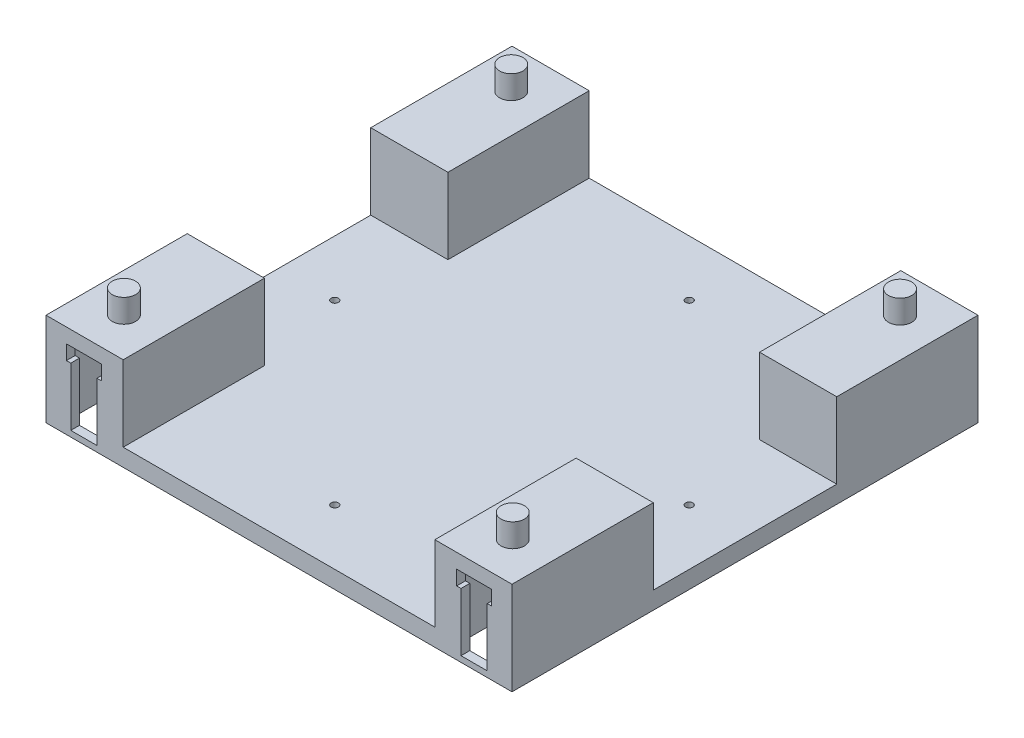
SolidWorks part; units mm, degrees
material "ABS"
ref_plane "Front Plane" through (0, 0, 0) normal (0, 0, 1) x (1, 0, 0)
ref_plane "Top Plane" through (0, 0, 0) normal (0, 1, 0) x (1, 0, 0)
ref_plane "Right Plane" through (0, 0, 0) normal (1, 0, 0) x (0, 0, -1)
sketch "Sketch2" plane through (0, 0, 0) normal (0, 1, 0) x (1, 0, 0)
  line L1 (-80, -80) -> (80, -80)
  line L2 (-80, -80) -> (-80, 80)
  line L3 (-80, 80) -> (80, 80)
  line L4 (80, -80) -> (80, 80)
  line L5 (-80, -80) -> (80, 80) construction
  line L6 (-80, 80) -> (80, -80) construction
  point P0 (0, 0)
  dimension "D1" = 160
  dimension "D2" = 160
extrude "Boss-Extrude2" add sketch "Sketch2" along normal blind 6
sketch "Sketch3" plane through (0, 0, 0) normal (0, 1, 0) x (1, 0, 0)
  line L22 (0, 25.1839) -> (0, 0) construction
  line L23 (-80, 80) -> (-53.5, 80)
  line L24 (-80, 80) -> (-80, 31.5)
  line L25 (-80, 31.5) -> (-53.5, 31.5)
  line L26 (-53.5, 80) -> (-53.5, 31.5)
  line L27 (0, 0) -> (14.719, 0) construction
  line L28 (53.5, 80) -> (53.5, 31.5)
  line L29 (80, 31.5) -> (53.5, 31.5)
  line L30 (80, 80) -> (80, 31.5)
  line L31 (80, 80) -> (53.5, 80)
  line L32 (80, -80) -> (53.5, -80)
  line L33 (80, -80) -> (80, -31.5)
  line L34 (80, -31.5) -> (53.5, -31.5)
  line L35 (53.5, -80) -> (53.5, -31.5)
  line L36 (-53.5, -80) -> (-53.5, -31.5)
  line L37 (-80, -31.5) -> (-53.5, -31.5)
  line L38 (-80, -80) -> (-80, -31.5)
  line L39 (-80, -80) -> (-53.5, -80)
  dimension "D1" = 26.5
  dimension "D2" = 48.5
extrude "Boss-Extrude3" add sketch "Sketch3" along normal blind 32
sketch "Sketch4" plane through (0, 0, 0) normal (0, 1, 0) x (1, 0, 0)
  line L8 (0, 18.9879) -> (0, 0) construction
  line L9 (-77, 77) -> (-56.5, 77)
  line L22 (-77, 77) -> (-77, 34.5)
  line L23 (-77, 34.5) -> (-56.5, 34.5)
  line L24 (-56.5, 77) -> (-56.5, 34.5)
  line L25 (0, 0) -> (16.3713, 0) construction
  line L26 (-80, 80) -> (-80, 31.5) construction
  line L27 (-53.5, 80) -> (-80, 80) construction
  line L29 (-53.5, 80) -> (-80, 31.5) construction
  line L30 (-56.5, 34.5) -> (-77, 77) construction
  line L31 (56.5, 34.5) -> (77, 77) construction
  line L32 (53.5, 80) -> (80, 31.5) construction
  line L33 (56.5, 77) -> (56.5, 34.5)
  line L34 (77, 34.5) -> (56.5, 34.5)
  line L35 (77, 77) -> (77, 34.5)
  line L36 (77, 77) -> (56.5, 77)
  line L37 (53.5, -80) -> (80, -31.5) construction
  line L38 (56.5, -34.5) -> (77, -77) construction
  line L39 (-56.5, -34.5) -> (-77, -77) construction
  line L40 (-53.5, -80) -> (-80, -31.5) construction
  line L41 (77, -77) -> (56.5, -77)
  line L42 (77, -77) -> (77, -34.5)
  line L43 (77, -34.5) -> (56.5, -34.5)
  line L44 (56.5, -77) -> (56.5, -34.5)
  line L45 (-56.5, -77) -> (-56.5, -34.5)
  line L46 (-77, -34.5) -> (-56.5, -34.5)
  line L47 (-77, -77) -> (-77, -34.5)
  line L48 (-77, -77) -> (-56.5, -77)
  point P11 (-66.75, 55.75)
  point P12 (-66.75, 55.75)
  dimension "D1" = 3
  dimension "D2" = 3
extrude "Cut-Extrude2" cut sketch "Sketch4" along normal blind 29
sketch "Sketch5" plane through (0, 32, 0) normal (0, 1, 0) x (1, 0, 0)
  line L0 (-66.75, 80) -> (-66.75, 66.5) construction
  line L1 (-80, 80) -> (-53.5, 80) construction
  line L2 (20.1859, 0) -> (0, 0) construction
  line L3 (0, 0) -> (0, 23.6816) construction
  line L4 (66.75, 80) -> (66.75, 66.5) construction
  line L5 (66.75, -80) -> (66.75, -66.5) construction
  line L6 (-66.75, -80) -> (-66.75, -66.5) construction
  circle A1 centre (-66.75, 66.5) radius 4
  circle A2 centre (66.75, 66.5) radius 4
  circle A3 centre (66.75, -66.5) radius 4
  circle A4 centre (-66.75, -66.5) radius 4
  dimension "D1" = 8
  dimension "D2" = 13.5
extrude "Boss-Extrude4" add sketch "Sketch5" along normal blind 8
sketch "Sketch6" plane through (0, 0, 80) normal (0, 0, 1) x (1, 0, 0)
  line L8 (-53.5, 6) -> (-80, 6) construction
  line L9 (-73, 27) -> (-61, 27)
  line L10 (-61, 27) -> (-61, 22)
  line L11 (-61, 22) -> (-62.5, 22)
  line L12 (-62.5, 22) -> (-62.5, 2)
  line L13 (-62.5, 2) -> (-71.5, 2)
  line L14 (-71.5, 2) -> (-71.5, 22)
  line L15 (-71.5, 22) -> (-73, 22)
  line L16 (-73, 22) -> (-73, 27)
  line L17 (-66.75, 6) -> (-66.75, 0) construction
  line L18 (-80, 0) -> (80, 0) construction
  line L19 (0, 0) -> (0, 22) construction
  line L20 (66.75, 6) -> (66.75, 0) construction
  line L21 (53.5, 6) -> (80, 6) construction
  line L22 (73, 22) -> (73, 27)
  line L23 (71.5, 22) -> (73, 22)
  line L24 (71.5, 2) -> (71.5, 22)
  line L25 (62.5, 2) -> (71.5, 2)
  line L26 (62.5, 22) -> (62.5, 2)
  line L27 (61, 22) -> (62.5, 22)
  line L28 (61, 27) -> (61, 22)
  line L29 (73, 27) -> (61, 27)
  line L30 (-80, 32) -> (-80, 0) construction
  dimension "D2" = 20
  dimension "D3" = 2
  dimension "D4" = 8.5
  dimension "D6" = 5
  dimension "D7" = 12
  dimension "D8" = 5
  dimension "D9" = 1.5
  dimension "D10" = 1.5
extrude "Cut-Extrude3" cut sketch "Sketch6" against normal blind 8
mirror "Mirror1" about plane through (0, 0, 0) normal (0, 0, 1) of "Cut-Extrude3"
sketch "Sketch7" plane through (0, 6, 0) normal (0, 1, 0) x (1, 0, 0)
  line L0 (0, 0) -> (-60.85, 0) construction
  line L1 (0, 0) -> (0, 60.85) construction
  line L2 (0, 0) -> (60.85, 0) construction
  line L3 (0, 0) -> (0, -60.85) construction
  circle A4 centre (-60.85, 0) radius 1.25
  circle A5 centre (0, 60.85) radius 1.25
  circle A6 centre (60.85, 0) radius 1.25
  circle A7 centre (0, -60.85) radius 1.25
  dimension "D2" = 4
  dimension "D1" = 2.5
  dimension "D3" = 60.85
extrude "Cut-Extrude4" cut sketch "Sketch7" against normal blind 10
